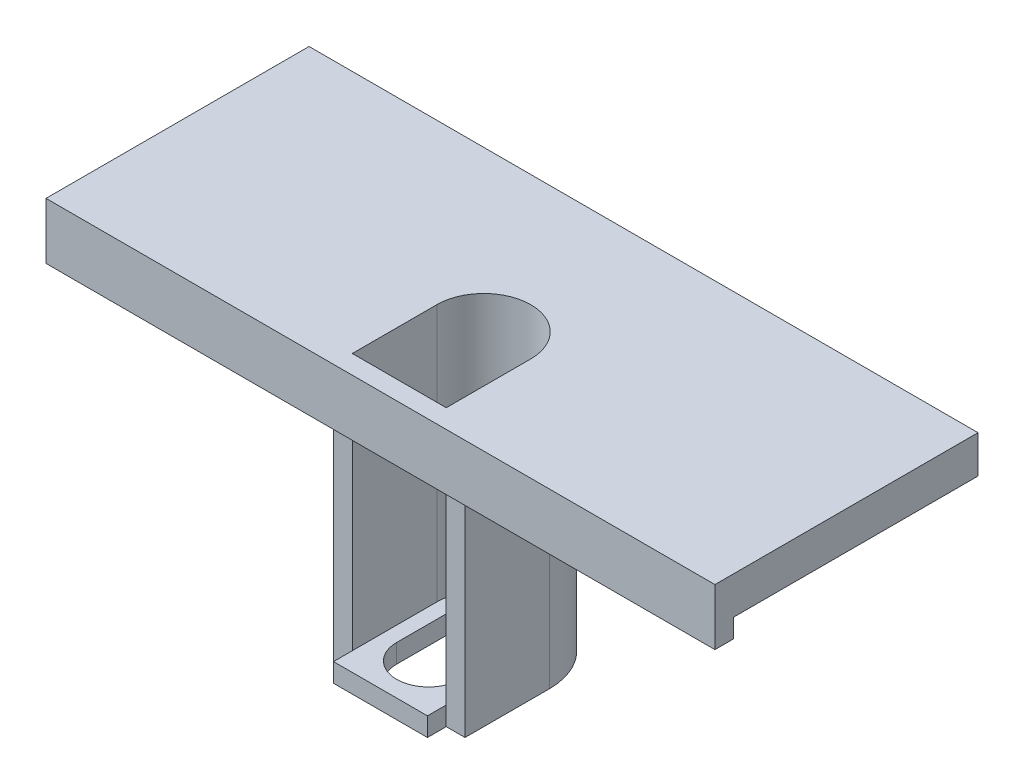
SolidWorks part; units mm, degrees
ref_plane "Front Plane" through (0, 0, 0) normal (0, 0, 1) x (1, 0, 0)
ref_plane "Top Plane" through (0, 0, 0) normal (0, 1, 0) x (1, 0, 0)
ref_plane "Right Plane" through (0, 0, 0) normal (1, 0, 0) x (0, 0, -1)
sketch "Sketch1" plane through (0, 0, 0) normal (0, 1, 0) x (1, 0, 0)
  line L0 (-4.445, 0) -> (4.445, 0) construction
  line L4 (22.606, 0) -> (22.606, 16.51)
  line L6 (22.606, 16.51) -> (-22.606, 16.51)
  line L7 (-22.606, 16.51) -> (-22.606, 0)
  line L10 (-4.445, 0) -> (-22.606, 0)
  line L11 (4.445, 0) -> (22.606, 0)
  line L12 (-4.445, 5.715) -> (-4.445, 0)
  line L13 (4.445, 5.715) -> (4.445, 0)
  arc A1 (4.445, 5.715) -> (-4.445, 5.715) centre (0, 5.715) ccw
  point P1 (-4.7235, 0)
  point P2 (0, 10.16)
  point P3 (5.4476, 0)
  point P6 (22.9376, 16.51)
  dimension "D1" = 45.212
  dimension "D2" = 22.606
  dimension "D3" = 16.51
  dimension "D4" = 10.16
  dimension "D6" = 4.445
extrude "Boss-Extrude1" add sketch "Sketch1" along normal blind 2.54
sketch "Sketch2" plane through (0, 0, 0) normal (0, 1, 0) x (1, 0, 0)
  line L0 (-4.445, 0) -> (-3.175, 0)
  line L1 (-3.175, 0) -> (-3.175, 5.715)
  line L2 (-4.445, 5.715) -> (-4.445, 0)
  line L3 (4.445, 5.715) -> (4.445, 0)
  line L4 (4.445, 0) -> (3.175, 0)
  line L5 (3.175, 0) -> (3.175, 5.715)
  arc A1 (4.445, 5.715) -> (-4.445, 5.715) centre (0, 5.715) ccw
  arc A2 (3.175, 5.715) -> (-3.175, 5.715) centre (0, 5.715) ccw
  arc A3 (4.445, 5.715) -> (-4.445, 5.715) centre (0, 5.715) ccw construction
  dimension "D1" = 1.27
extrude "Boss-Extrude2" add sketch "Sketch2" against normal blind 18.669 from surface at 2.54 starting at face at (0, 2.54, -6.1119)
sketch "Sketch3" plane through (0, 0, 0) normal (0, 0, 1) x (1, 0, 0)
  line L0 (-22.606, 2.54) -> (-22.606, -1.27)
  line L1 (-22.606, -1.27) -> (22.606, -1.27)
  line L2 (22.606, -1.27) -> (22.606, 2.54)
  line L3 (22.606, 2.54) -> (-22.606, 2.54)
  dimension "D1" = 3.81
extrude "Boss-Extrude3" add sketch "Sketch3" along normal blind 1.27
sketch "Sketch4" plane through (0, 0, 0) normal (0, 1, 0) x (1, 0, 0)
  line L0 (3.175, 5.715) -> (3.175, -1.27)
  line L1 (22.606, -1.27) -> (-22.606, -1.27) construction
  line L2 (3.175, -1.27) -> (-3.175, -1.27)
  line L3 (-3.175, -1.27) -> (-3.175, 5.715)
  line L4 (-2.159, 5.715) -> (-2.159, 1.9829)
  line L5 (2.159, 5.715) -> (2.159, 1.9829)
  arc A0 (3.175, 5.715) -> (-3.175, 5.715) centre (0, 5.715) ccw
  arc A1 (2.159, 5.715) -> (-2.159, 5.715) centre (0, 5.715) ccw
  arc A2 (-2.159, 1.9829) -> (2.159, 1.9829) centre (0, 1.9829) ccw
  dimension "D1" = 4.318
  dimension "D2" = 3.7321
extrude "Boss-Extrude4" add sketch "Sketch4" along normal blind 1.27 from surface at -16.129 starting at face at (0, -16.129, -3.81)
